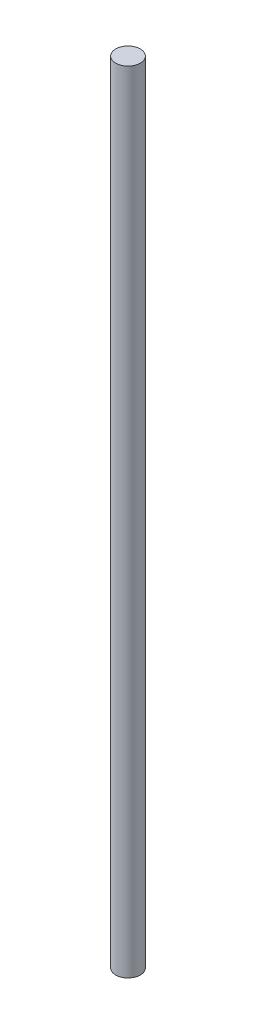
SolidWorks part; units mm, degrees
ref_plane "Front Plane" through (0, 0, 0) normal (0, 0, 1) x (1, 0, 0)
ref_plane "Top Plane" through (0, 0, 0) normal (0, 1, 0) x (1, 0, 0)
ref_plane "Right Plane" through (0, 0, 0) normal (1, 0, 0) x (0, 0, -1)
sketch "Sketch1" plane through (0, 0, 0) normal (0, 1, 0) x (1, 0, 0)
  circle A0 centre (0, 0) radius 2.375
  dimension "D1" = 4.75
extrude "Boss-Extrude1" add sketch "Sketch1" along normal blind 152.4
